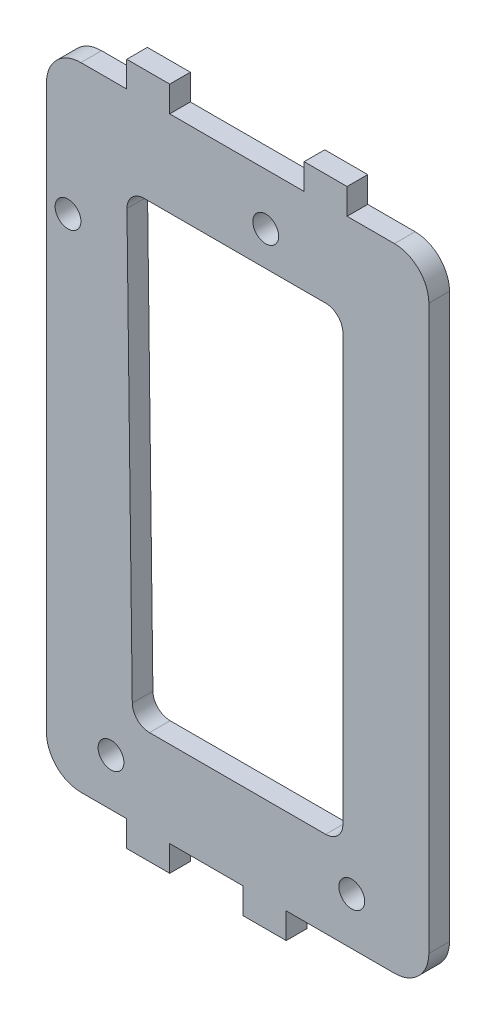
SolidWorks part; units mm, degrees
ref_plane "Alzado" through (0, 0, 0) normal (0, 0, 1) x (1, 0, 0)
ref_plane "Planta" through (0, 0, 0) normal (0, 1, 0) x (1, 0, 0)
ref_plane "Vista lateral" through (0, 0, 0) normal (1, 0, 0) x (0, 0, -1)
sketch "Croquis1" plane through (0, 0, 0) normal (0, 0, 1) x (1, 0, 0)
  line L0 (-27.7352, 52.6459) -> (-43.3652, 52.6459)
  line L1 (-48.3652, -20.8541) -> (-48.3652, -23.8541)
  line L2 (-48.3652, -23.8541) -> (-43.3652, -23.8541)
  line L3 (-43.3652, -23.8541) -> (-43.3652, -20.8541)
  line L4 (-34.8152, -23.8541) -> (-34.8152, -20.8541)
  line L5 (-34.8152, -20.8541) -> (-43.3652, -20.8541)
  line L6 (-57.6952, 48.6459) -> (-57.6952, -16.8541)
  line L8 (-34.8152, -23.8541) -> (-29.8152, -23.8541)
  line L9 (-29.8152, -23.8541) -> (-29.8152, -20.8541)
  line L10 (-29.8152, -20.8541) -> (-17.2252, -20.8541)
  line L12 (-27.7352, 55.6459) -> (-22.7352, 55.6459)
  line L13 (-48.3652, -20.8541) -> (-53.6952, -20.8541)
  line L14 (-13.2252, 48.6459) -> (-13.2252, -16.8541)
  line L16 (-22.7352, 55.6459) -> (-22.7352, 52.6459)
  line L17 (-27.7352, 55.6459) -> (-27.7352, 52.6459)
  line L18 (-22.7352, 52.6459) -> (-17.2252, 52.6459)
  line L20 (-35.5502, 42.6459) -> (-25.2252, 42.6459)
  line L21 (-23.2252, 40.6459) -> (-23.2252, -8.8541)
  line L22 (-25.2252, -10.8541) -> (-45.7201, -10.8541)
  line L23 (-47.7199, -8.8792) -> (-48.3399, 40.6208)
  line L24 (-46.34, 42.6459) -> (-35.5502, 42.6459)
  line L27 (-53.6952, 52.6459) -> (-48.3652, 52.6459)
  line L28 (-48.3652, 52.6459) -> (-48.3652, 55.6459)
  line L29 (-48.3652, 55.6459) -> (-43.3652, 55.6459)
  line L30 (-43.3652, 55.6459) -> (-43.3652, 52.6459)
  arc A0 (-53.6952, -20.8541) -> (-57.6952, -16.8541) centre (-53.6952, -16.8541) cw
  arc A1 (-13.2252, -16.8541) -> (-17.2252, -20.8541) centre (-17.2252, -16.8541) cw
  arc A2 (-17.2252, 52.6459) -> (-13.2252, 48.6459) centre (-17.2252, 48.6459) cw
  arc A3 (-57.6952, 48.6459) -> (-53.6952, 52.6459) centre (-53.6952, 48.6459) cw
  arc A4 (-23.2252, -8.8541) -> (-25.2252, -10.8541) centre (-25.2252, -8.8541) cw
  arc A5 (-25.2252, 42.6459) -> (-23.2252, 40.6459) centre (-25.2252, 40.6459) cw
  arc A6 (-48.3399, 40.6208) -> (-46.34, 42.6459) centre (-46.34, 40.6459) cw
  arc A7 (-45.7201, -10.8541) -> (-47.7199, -8.8792) centre (-45.7201, -8.8541) cw
  circle A8 centre (-55.1952, 36.6459) radius 1.5
  circle A9 centre (-50.1952, -15.3541) radius 1.5
  circle A10 centre (-22.1952, -15.3541) radius 1.5
  point P47 (-8.5252, 49.1459)
  dimension "D1" = 4
  dimension "D2" = 2
extrude "Saliente-Extruir1" add sketch "Croquis1" along normal blind 2.4
sketch "Croquis2" plane through (0, 0, 2.4) normal (0, 0, 1) x (1, 0, 0)
  circle A0 centre (-32.1952, 46.6459) radius 1.5
extrude "Cortar-Extruir1" cut sketch "Croquis2" against normal up to next
